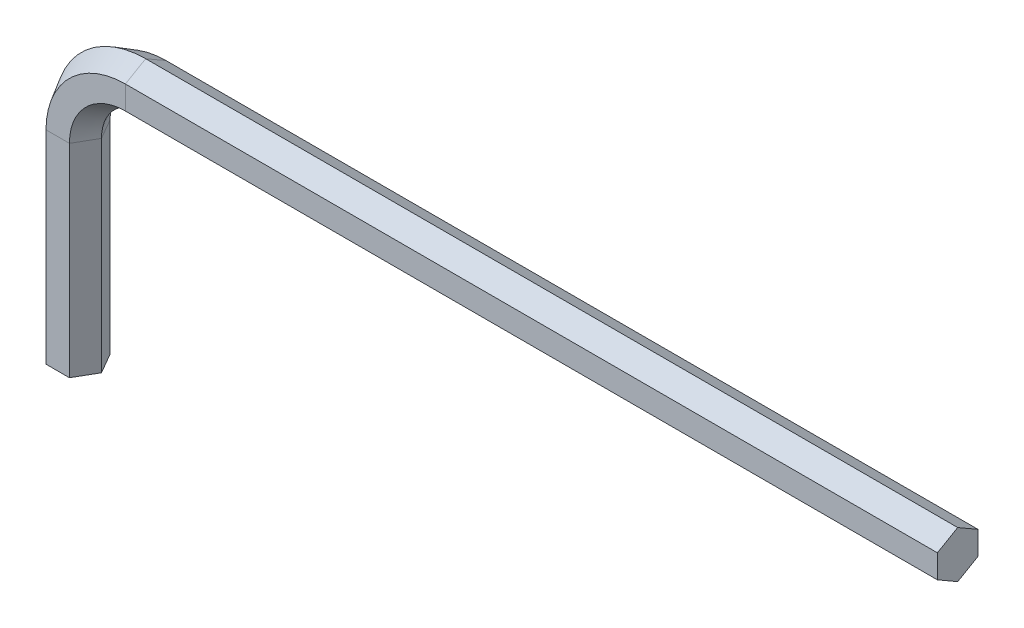
SolidWorks part; units mm, degrees
ref_plane "Front Plane" through (0, 0, 0) normal (0, 0, 1) x (1, 0, 0)
ref_plane "Top Plane" through (0, 0, 0) normal (0, 1, 0) x (1, 0, 0)
ref_plane "Right Plane" through (0, 0, 0) normal (1, 0, 0) x (0, 0, -1)
sketch "Sketch1" plane through (0, 0, 0) normal (0, 0, 1) x (1, 0, 0)
  line L0 (0, 0) -> (0, 15)
  line L1 (5, 20) -> (65, 20)
  arc A0 (5, 20) -> (0, 15) centre (5, 15) ccw
  point P6 (0, 20)
  dimension "D3" = 5
  dimension "D1" = 65
  dimension "D2" = 20
sketch "Sketch2" plane through (0, 0, 0) normal (0, 1, 0) x (1, 0, 0)
  line L0 (0, 0) -> (1.7321, 0) construction
  line L1 (0.866, -1.5) -> (1.7321, 0)
  line L2 (1.7321, 0) -> (0.866, 1.5)
  line L3 (0.866, 1.5) -> (-0.866, 1.5)
  line L4 (-0.866, 1.5) -> (-1.7321, 0)
  line L5 (-1.7321, 0) -> (-0.866, -1.5)
  line L6 (-0.866, -1.5) -> (0.866, -1.5)
  circle A0 centre (0, 0) radius 1.5 construction
  dimension "D1" = 1.7321
sweep "Sweep1" add profiles "Sketch2" path "Sketch1"
